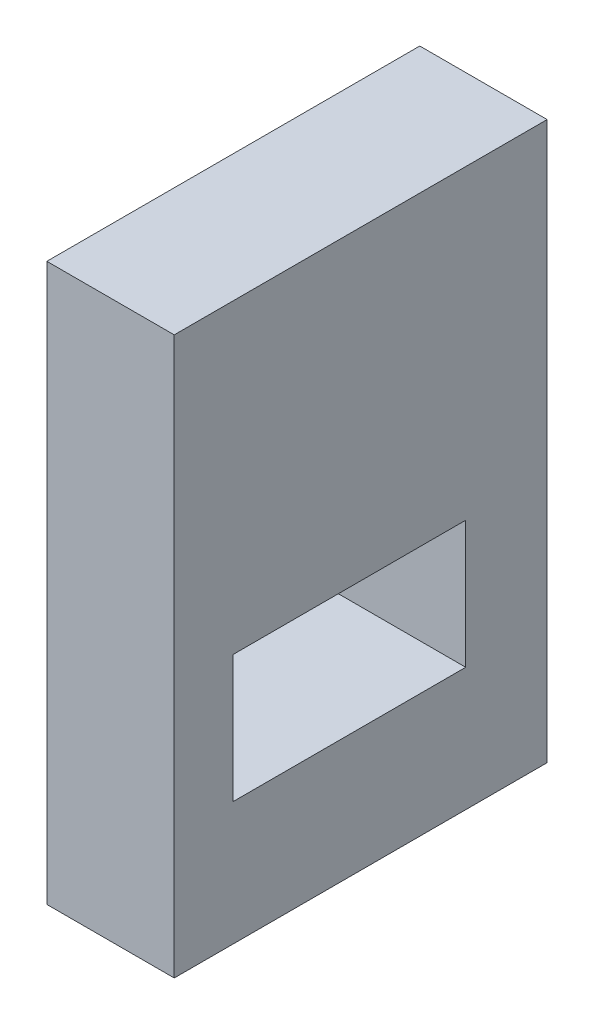
SolidWorks part; units mm, degrees
ref_plane "前视基准面" through (0, 0, 0) normal (0, 0, 1) x (1, 0, 0)
ref_plane "上视基准面" through (0, 0, 0) normal (0, 1, 0) x (1, 0, 0)
ref_plane "右视基准面" through (0, 0, 0) normal (1, 0, 0) x (0, 0, -1)
sketch "Sketch1" plane through (0, 0, 0) normal (0, 1, 0) x (1, 0, 0)
  line L0 (-57.9417, 37.7357) -> (54.7301, 37.7357)
  line L1 (-81.7606, -53.5258) -> (114.4114, -53.5258)
  spline S0 degree 3 poles (-25.2909, 37.7357) (-30.7619, 7.5366) (-30.1308, -23.0685) (-31.9817, -53.5258) knots 0 0 0 0 1 1 1 1
  spline S1 degree 3 poles (28.2348, 37.7357) (39.488, 7.9685) (30.1141, -23.185) (35.9961, -53.5258) knots 0 0 0 0 1 1 1 1
sketch "Sketch2" plane through (0, 0, 0) normal (1, 0, 0) x (0, 0, -1)
  line L1 (69.6979, -98.4177) -> (-76.679, -98.4177)
  line L2 (69.6979, -98.4177) -> (69.6979, 120.215)
  line L3 (69.6979, 120.215) -> (-76.679, 120.215)
  line L4 (-76.679, -98.4177) -> (-76.679, 120.215)
  point P4 (69.6979, 120.215)
extrude "Boss-Extrude2" add sketch "Sketch2" along normal mid plane 50
extrude "Cut-Extrude1" cut sketch "Sketch1" against normal blind 50 contours S1 L0 S0 L1
